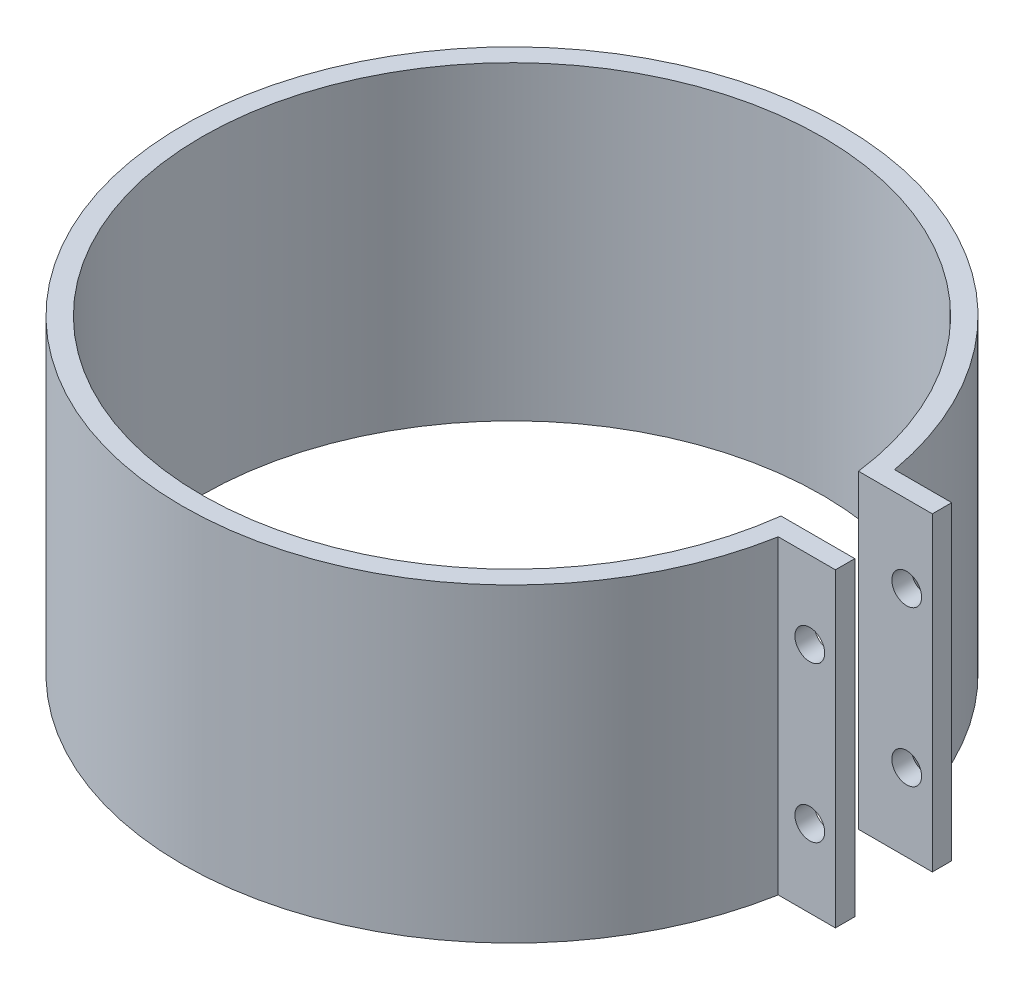
SolidWorks part; units mm, degrees
ref_plane "Front" through (0, 0, 0) normal (0, 0, 1) x (1, 0, 0)
ref_plane "Top" through (0, 0, 0) normal (0, 1, 0) x (1, 0, 0)
ref_plane "Right" through (0, 0, 0) normal (1, 0, 0) x (0, 0, -1)
sketch "Sketch2" plane through (0, 0, 0) normal (0, 1, 0) x (1, 0, 0)
  line L0 (50.8, 0) -> (62.4902, 0) construction
  line L1 (53.6002, -6.35) -> (62.4902, -6.35)
  line L2 (53.6002, 6.35) -> (62.4902, 6.35)
  line L3 (50.8, 6.35) -> (62.4902, 6.35) construction
  line L4 (50.8, -6.35) -> (62.4902, -6.35) construction
  line L5 (53.6002, -6.35) -> (50.4016, -6.35)
  line L6 (53.6002, 6.35) -> (50.4016, 6.35)
  line L7 (53.6002, 9.525) -> (62.4902, 9.525)
  line L8 (53.6002, 9.525) -> (53.1279, 9.525)
  line L9 (62.4902, 9.525) -> (62.4902, 6.35)
  line L10 (53.6002, -9.525) -> (53.1279, -9.525)
  line L11 (53.6002, -9.525) -> (62.4902, -9.525)
  line L12 (62.4902, -6.35) -> (62.4902, -9.525)
  line L13 (53.6002, -9.525) -> (50.4016, -9.525) construction
  line L14 (53.6002, 9.525) -> (50.4016, 9.525) construction
  arc A0 (50.4016, 6.35) -> (50.4016, -6.35) centre (0, 0) ccw
  arc A1 (53.1279, 9.525) -> (53.1279, -9.525) centre (0, 0) ccw
  circle A2 centre (0, 0) radius 53.975 construction
  circle A3 centre (0, 0) radius 50.8 construction
  dimension "D1" = 101.6
  dimension "D6" = 8.89
  dimension "D7" = 3.175
  dimension "D2" = 3.175
  dimension "D3" = 6.35
  dimension "D4" = 6.35
  dimension "D5" = 3.175
extrude "Boss-Extrude1" add sketch "Sketch2" along normal blind 50.8
sketch "Sketch3" plane through (0, 0, 9.525) normal (0, 0, 1) x (1, 0, 0)
  line L0 (58.2922, 50.8) -> (58.2922, 0) construction
  line L1 (53.1279, 50.8) -> (62.4902, 50.8) construction
  line L2 (53.1279, 0) -> (62.4902, 0) construction
  circle A0 centre (58.2922, 38.1) radius 2.4384
  circle A1 centre (58.2922, 12.7) radius 2.4384
  dimension "D1" = 4.8768
  dimension "D2" = 12.7
  dimension "D3" = 12.7
extrude "Cut-Extrude1" cut sketch "Sketch3" against normal through all
